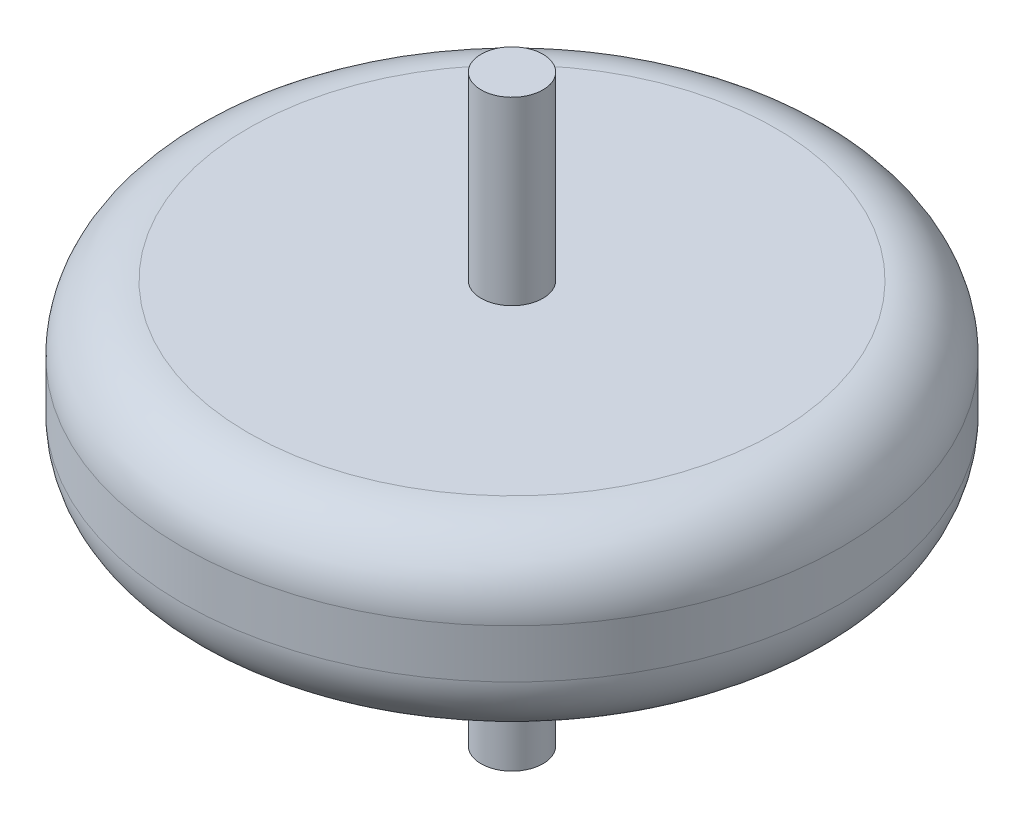
SolidWorks part; units mm, degrees
ref_plane "Front Plane" through (0, 0, 0) normal (0, 0, 1) x (1, 0, 0)
ref_plane "Top Plane" through (0, 0, 0) normal (0, 1, 0) x (1, 0, 0)
ref_plane "Right Plane" through (0, 0, 0) normal (1, 0, 0) x (0, 0, -1)
sketch "Sketch1" plane through (0, 0, 0) normal (0, 1, 0) x (1, 0, 0)
  circle A0 centre (0, 0) radius 101.6
  dimension "D1" = 203.2
extrude "Boss-Extrude1" add sketch "Sketch1" along normal mid plane 55.626
sketch "Sketch2" plane through (0, 27.813, 0) normal (0, 1, 0) x (1, 0, 0)
  circle A0 centre (0, 0) radius 9.525
  dimension "D1" = 19.05
extrude "Boss-Extrude2" add sketch "Sketch2" along normal blind 55.626 and the other way blind 124.206
fillet "Fillet1" radius 20.32 2 edges at (0, -27.813, 101.6) (0, 27.813, 101.6)
